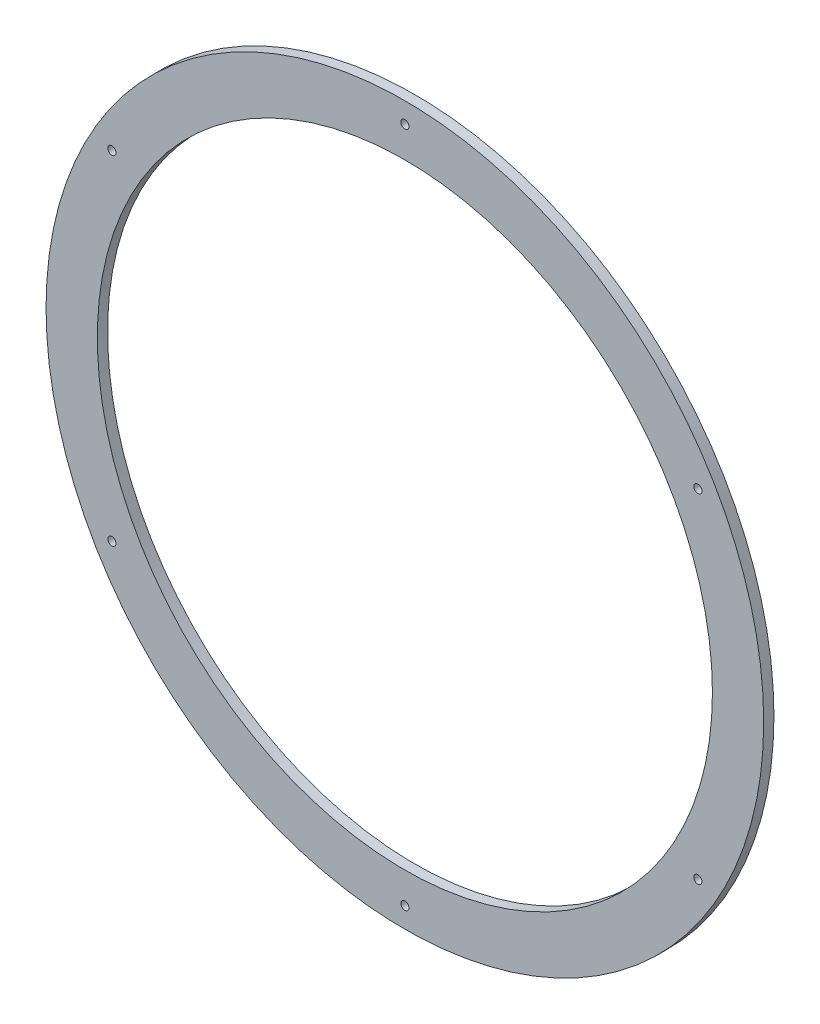
SolidWorks part; units mm, degrees
material "Plastique personnalisé"
ref_plane "Plan de face" through (0, 0, 0) normal (0, 0, 1) x (1, 0, 0)
ref_plane "Plan de dessus" through (0, 0, 0) normal (0, 1, 0) x (1, 0, 0)
ref_plane "Plan de droite" through (0, 0, 0) normal (1, 0, 0) x (0, 0, -1)
sketch "Esquisse1" plane through (0, 0, 0) normal (0, 0, 1) x (1, 0, 0)
  circle A0 centre (0, 0) radius 175
  circle A1 centre (0, 0) radius 150
  dimension "D1" = 350
  dimension "D2" = 300
extrude "Boss.-Extru.1" add sketch "Esquisse1" along normal blind 5
sketch "Esquisse2" plane through (0, 0, 5) normal (0, 0, 1) x (1, 0, 0)
  line L0 (0, 0) -> (0, 175)
  line L1 (0, 175) -> (0, 165)
  circle A0 centre (0, 0) radius 175 construction
  circle A1 centre (0, 165) radius 2
  circle A2 centre (142.8942, 82.5) radius 2
  circle A3 centre (142.8942, -82.5) radius 2
  circle A4 centre (0, -165) radius 2
  circle A5 centre (-142.8942, -82.5) radius 2
  circle A6 centre (-142.8942, 82.5) radius 2
  point P21 (0, 0)
  dimension "D2" = 4
  dimension "D1" = 10
  dimension "D3" = 6
extrude "Enlèv. mat.-Extru.1" cut sketch "Esquisse2" against normal blind 10 contours A1 | A6 | A5 | A4 | A3 | A2
